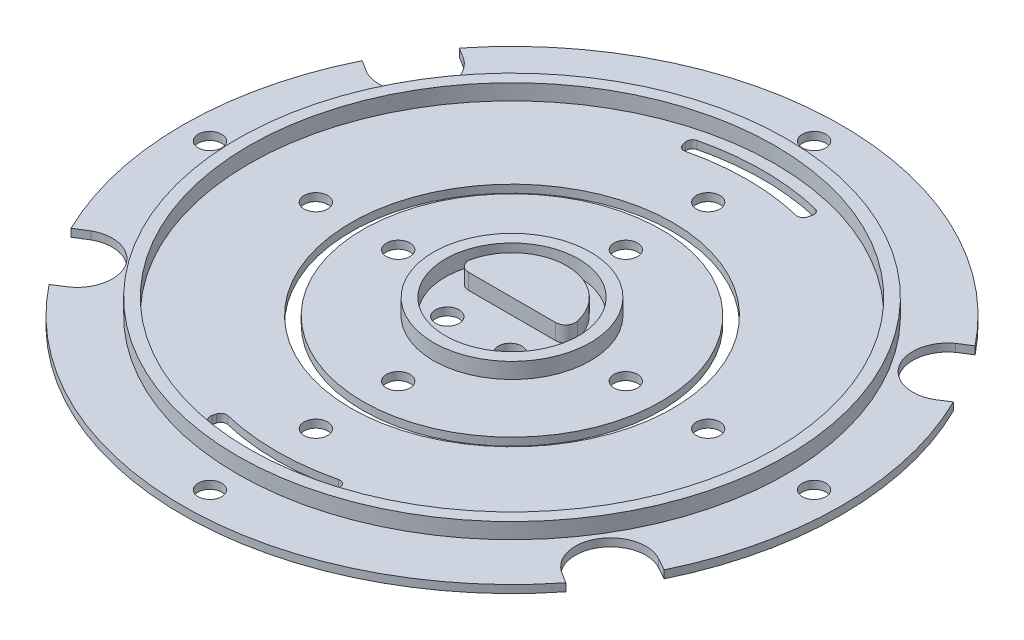
SolidWorks part; units mm, degrees
ref_plane "Front Plane" through (0, 0, 0) normal (0, 0, 1) x (1, 0, 0)
ref_plane "Top Plane" through (0, 0, 0) normal (0, 1, 0) x (1, 0, 0)
ref_plane "Right Plane" through (0, 0, 0) normal (1, 0, 0) x (0, 0, -1)
sketch "Эскиз1" plane through (0, 0, 0) normal (0, 1, 0) x (1, 0, 0)
  circle A0 centre (0, 0) radius 35
extrude "Бобышка-Вытянуть1" add sketch "Эскиз1" along normal blind 2
sketch "Эскиз2" plane through (0, 2, 0) normal (0, 1, 0) x (1, 0, 0)
  line L0 (0, 0) -> (-24.7487, 24.7487) construction
  line L17 (5.5656, 0) -> (-5.5656, 0)
  arc A2 (6.797, 1.542) -> (5.5656, 0) centre (5.5656, 1.2626) cw
  arc A17 (-6.797, 1.542) -> (6.797, 1.542) centre (0, 0) cw
  arc A18 (-5.5656, 0) -> (-6.797, 1.542) centre (-5.5656, 1.2626) cw
  circle A19 centre (0, 0) radius 8.4903
  circle A20 centre (0, 0) radius 10
  circle A21 centre (0, 0) radius 35 construction
  circle A30 centre (0, 0) radius 35
  circle A31 centre (0, 0) radius 33.5
  point P34 (0, 0.8588)
  dimension "D1" = 16.9805
  dimension "D2" = 20
  dimension "D4" = 1.2626
  dimension "D5" = 6.9697
extrude "Вырез-Вытянуть1" cut sketch "Эскиз2" against normal blind 2
sketch "Эскиз5" plane through (0, 0, 0) normal (0, -1, 0) x (1, 0, 0)
  circle A0 centre (0, 0) radius 42
  circle A1 centre (0, 0) radius 35 construction
  dimension "D1" = 84
extrude "Бобышка-Вытянуть3" add sketch "Эскиз5" along normal blind 2
sketch "Эскиз6" plane through (0, -2, 0) normal (0, -1, 0) x (1, 0, 0)
  line L35 (0, 0) -> (-34, -21.5643) construction
  line L36 (0, 0) -> (-34, 21.4357) construction
  line L37 (0, 0) -> (34, -21.5643) construction
  line L38 (0, 0) -> (34, 21.4357) construction
  line L40 (-36.1337, -17.6023) -> (-37.6688, -18.5759)
  line L41 (-31.3255, -25.1833) -> (-32.8606, -26.1569)
  line L44 (31.3255, -25.1833) -> (32.8606, -26.1569)
  line L45 (36.1337, -17.6023) -> (37.6688, -18.5759)
  line L46 (31.3907, 25.102) -> (32.9284, 26.0714)
  line L47 (36.1831, 17.5007) -> (37.7654, 18.3786)
  line L48 (-31.3907, 25.102) -> (-32.9284, 26.0714)
  line L49 (-36.1831, 17.5007) -> (-37.7207, 18.4701)
  arc A38 (-31.3255, -25.1833) -> (-36.1337, -17.6023) centre (-34, -21.5643) ccw
  arc A40 (-36.1831, 17.5007) -> (-31.3907, 25.102) centre (-34, 21.4357) ccw
  arc A42 (31.3907, 25.102) -> (36.1831, 17.5007) centre (34, 21.4357) ccw
  arc A43 (36.1337, -17.6023) -> (31.3255, -25.1833) centre (34, -21.5643) ccw
  arc A49 (-37.6688, -18.5759) -> (-32.8606, -26.1569) centre (0, 0) ccw
  arc A50 (-32.9284, 26.0714) -> (-37.7207, 18.4701) centre (0, 0) ccw
  arc A51 (37.7654, 18.3786) -> (32.9284, 26.0714) centre (0, 0) ccw
  arc A52 (32.8606, -26.1569) -> (37.6688, -18.5759) centre (0, 0) ccw
  point P20 (0, 0)
  point P25 (0, 0)
  point P38 (34, -21.5643)
  point P39 (0, 0)
  point P40 (34, 21.4357)
extrude "Вырез-Вытянуть3" cut sketch "Эскиз6" against normal up to surface (2 mm away) up to face at (0, 0, -1.9798)
sketch "Эскиз7" plane through (0, 0, 0) normal (0, 1, 0) x (1, 0, 0)
  line L0 (0, 0) -> (0, 25) construction
  line L1 (0, 0) -> (0, -8.4903) construction
  line L2 (0, 0) -> (25, 0) construction
  line L3 (0, 0) -> (-25, 0) construction
  line L5 (0, -23.5) -> (0, -25) construction
  line L6 (0, -4.2451) -> (4, -4.2451) construction
  line L7 (0, -4.2451) -> (-4, -4.2451) construction
  line L8 (5.5656, 0) -> (-5.5656, 0) construction
  circle A5 centre (0, 25) radius 1.5
  circle A6 centre (-25, 0) radius 1.5
  circle A7 centre (25, 0) radius 1.5
  circle A8 centre (0, -25) radius 1.5
  circle A10 centre (4, -4.2451) radius 1.5
  circle A11 centre (-4, -4.2451) radius 1.5
  dimension "D1" = 3
  dimension "D2" = 25
  dimension "D3" = 25
extrude "Вырез-Вытянуть4" cut sketch "Эскиз7" against normal up to surface (2 mm away) up to face at (0.0014, -2, -0.0516)
sketch "Эскиз9" plane through (0, 0, 0) normal (0, 1, 0) x (1, 0, 0)
  line L0 (-4.2875, -42.5446) -> (27.7125, -42.5446) construction
  line L1 (0, 0) -> (-15.5268, 0) construction
  line L2 (-7.9563, -29.6934) -> (-8.0858, -30.1765)
  line L3 (7.9563, -29.6934) -> (8.0858, -30.1765)
  line L4 (7.9563, 29.6934) -> (8.0858, 30.1765)
  line L5 (-7.9563, 29.6934) -> (-8.0858, 30.1765)
  arc A0 (-7.538, -31.0995) -> (7.538, -31.0995) centre (0, 0) ccw
  arc A1 (-7.0555, -29.1585) -> (7.0555, -29.1585) centre (0, 0) ccw
  arc A2 (8.0858, -30.1765) -> (7.538, -31.0995) centre (7.3613, -30.3706) cw
  arc A3 (7.9563, -29.6934) -> (7.0555, -29.1585) centre (7.2319, -29.8875) ccw
  arc A4 (-7.538, -31.0995) -> (-8.0858, -30.1765) centre (-7.3613, -30.3706) cw
  arc A5 (-7.9563, -29.6934) -> (-7.0555, -29.1585) centre (-7.2319, -29.8875) cw
  arc A6 (-7.9563, 29.6934) -> (-7.0555, 29.1585) centre (-7.2319, 29.8875) ccw
  arc A7 (-7.538, 31.0995) -> (-8.0858, 30.1765) centre (-7.3613, 30.3706) ccw
  arc A8 (7.9563, 29.6934) -> (7.0555, 29.1585) centre (7.2319, 29.8875) cw
  arc A9 (8.0858, 30.1765) -> (7.538, 31.0995) centre (7.3613, 30.3706) ccw
  arc A10 (-7.0555, 29.1585) -> (7.0555, 29.1585) centre (0, 0) cw
  arc A11 (-7.538, 31.0995) -> (7.538, 31.0995) centre (0, 0) cw
  point P27 (-8.2822, 30.9096)
  point P28 (8.2822, 30.9096)
  dimension "D1" = 0.75
extrude "Вырез-Вытянуть5" cut sketch "Эскиз9" against normal up to surface (2 mm away) up to face at (0, -2, -26.5)
sketch "Эскиз10" plane through (0, 0, 0) normal (0, 1, 0) x (1, 0, 0)
  circle A0 centre (0, 0) radius 19
  circle A1 centre (0, 0) radius 20.5
  dimension "D1" = 38
  dimension "D2" = 41
extrude "Вырез-Вытянуть6" cut sketch "Эскиз10" against normal up to surface (2 mm away) up to face at (0, -2, 30.2327)
sketch "Эскиз11" plane through (0, 0, 0) normal (0, 1, 0) x (1, 0, 0)
  line L0 (0, 0) -> (0, 14.5) construction
  circle A0 centre (0, 14.5) radius 1.5
  circle A1 centre (14.5, 0) radius 1.5
  circle A2 centre (0, -14.5) radius 1.5
  circle A3 centre (-14.5, 0) radius 1.5
  point P13 (0, 0)
  dimension "D1" = 4
  dimension "D2" = 3
  dimension "D3" = 21.297
extrude "Вырез-Вытянуть7" cut sketch "Эскиз11" against normal up to surface (2 mm away) up to face at (4, -2, 2.7451)
sketch "Эскиз12" plane through (0, 0, 0) normal (0, 1, 0) x (1, 0, 0)
  circle A6 centre (0, -38.5) radius 1.5
  circle A7 centre (-38.5, 0) radius 1.5
  circle A8 centre (0, 38.5) radius 1.5
  circle A9 centre (38.5, 0) radius 1.5
  point P11 (0, 0)
  point P16 (0, 0)
extrude "Вырез-Вытянуть8" cut sketch "Эскиз12" against normal up to surface (2 mm away) up to face at (0, -2, -20.5)
sketch "Эскиз13" plane through (0, -2, 0) normal (0, -1, 0) x (1, 0, 0)
  circle A0 centre (0, 0) radius 42
extrude "Вырез-Вытянуть9" cut sketch "Эскиз13" against normal blind 1
sketch "Эскиз15" plane through (0, -1, 0) normal (0, -1, 0) x (1, 0, 0)
  circle A0 centre (21.9999, 21.9356) radius 2
  circle A1 centre (21.9999, -22.0642) radius 2
  circle A2 centre (-21.9999, -22.0642) radius 2
  circle A3 centre (-21.9999, 21.9358) radius 2
  circle A4 centre (-0.0001, 4.1858) radius 2
  point P8 (0, 0)
extrude "Бобышка-Вытянуть5" add sketch "Эскиз15" along normal blind 4
